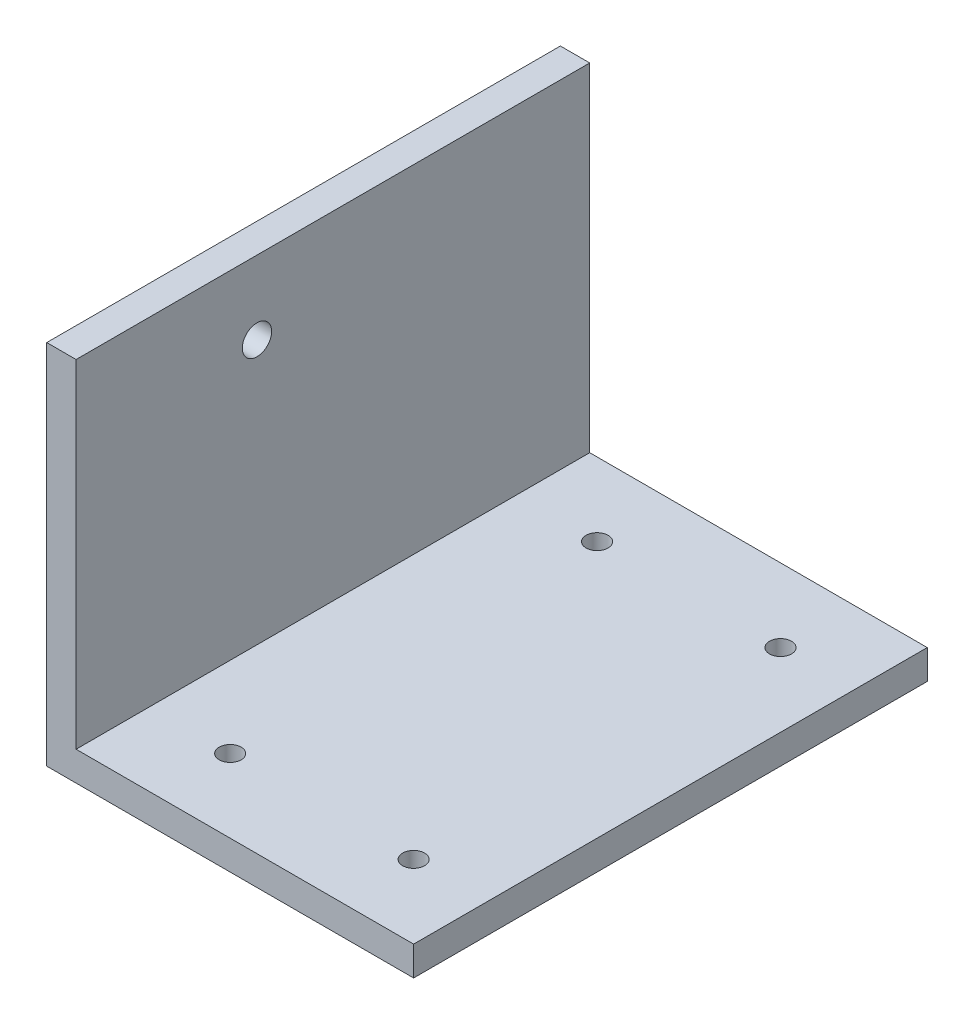
SolidWorks part; units mm, degrees
ref_plane "Plan de face" through (0, 0, 0) normal (0, 0, 1) x (1, 0, 0)
ref_plane "Plan de dessus" through (0, 0, 0) normal (0, 1, 0) x (1, 0, 0)
ref_plane "Plan de droite" through (0, 0, 0) normal (1, 0, 0) x (0, 0, -1)
sketch "Esquisse1" plane through (0, 0, 0) normal (0, 0, 1) x (1, 0, 0)
  line L1 (0, 0) -> (4, 0)
  line L2 (0, 0) -> (0, 50)
  line L3 (0, 50) -> (4, 50)
  line L4 (4, 4) -> (4, 50)
  line L5 (4, 0) -> (50, 0)
  line L7 (4, 4) -> (50, 4)
  line L8 (50, 0) -> (50, 4)
  dimension "D1" = 50
  dimension "D2" = 4
  dimension "D3" = 4
  dimension "D4" = 46
extrude "Extrusion1" add sketch "Esquisse1" along normal blind 70
sketch "Esquisse2" plane through (0, 4, 0) normal (0, 1, 0) x (1, 0, 0)
  line L0 (50, -70) -> (4, -70) construction
  line L1 (50, -70) -> (50, 0) construction
  circle A0 centre (40, -60) radius 1.5
  dimension "D1" = 3
  dimension "D2" = 10
  dimension "D3" = 10
extrude "Extrusion2" cut sketch "Esquisse2" against normal through all
pattern_linear "Répétition linéaire1" count 2 spacing 50 along (0, 0, -1) count 2 spacing 25 along (-1, 0, 0) of "Extrusion2"
sketch "Esquisse3" plane through (0, 0, 0) normal (-1, 0, 0) x (0, 0, 1)
  circle A0 centre (45.35, 40) radius 2
extrude "Enlèv. mat.-Extru.1" cut sketch "Esquisse3" against normal through all
